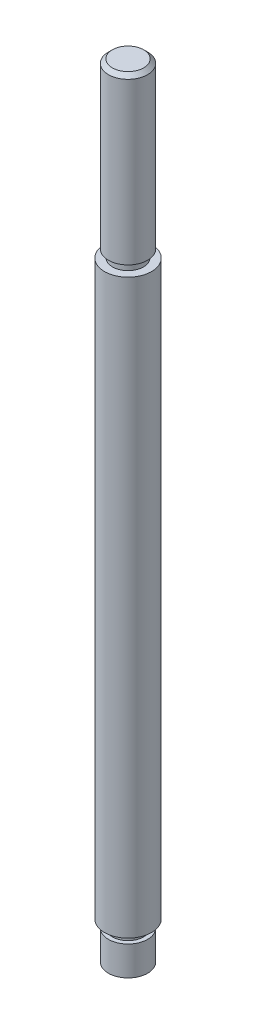
SolidWorks part; units mm, degrees
ref_plane "Front Plane" through (0, 0, 0) normal (0, 0, 1) x (1, 0, 0)
ref_plane "Top Plane" through (0, 0, 0) normal (0, 1, 0) x (1, 0, 0)
ref_plane "Right Plane" through (0, 0, 0) normal (1, 0, 0) x (0, 0, -1)
sketch "Sketch1" plane through (0, 0, 0) normal (0, 0, 1) x (1, 0, 0)
  line L0 (0, 0) -> (0, 117.9125) construction
  line L1 (0, 0) -> (5, 0)
  line L2 (3.95, 9.5) -> (3.95, 7.5)
  line L3 (3.95, 9.5) -> (6, 9.5)
  line L4 (6, 9.5) -> (6, 155.5)
  line L6 (0, 0) -> (0, 199.5)
  line L7 (3.95, 7.5) -> (5, 7.5)
  line L8 (5, 7.5) -> (5, 0)
  line L9 (6, 155.5) -> (3.95, 155.5)
  line L10 (3.95, 155.5) -> (3.95, 157.5)
  line L11 (3.95, 157.5) -> (5, 157.5)
  line L12 (5, 157.5) -> (5, 199.5)
  line L13 (5, 199.5) -> (0, 199.5)
  dimension "D1" = 9.5
  dimension "D2" = 12
  dimension "D3" = 2
  dimension "D4" = 2
  dimension "D5" = 5
  dimension "D6" = 3.95
  dimension "D7" = 3.95
  dimension "D8" = 148
  dimension "D9" = 42
  dimension "D10" = 5
revolve "Revolve1" add sketch "Sketch1" angle 360 about L0
chamfer "Chamfer1" distance 1 angle 45 1 edges at (0, 199.5, -5)
